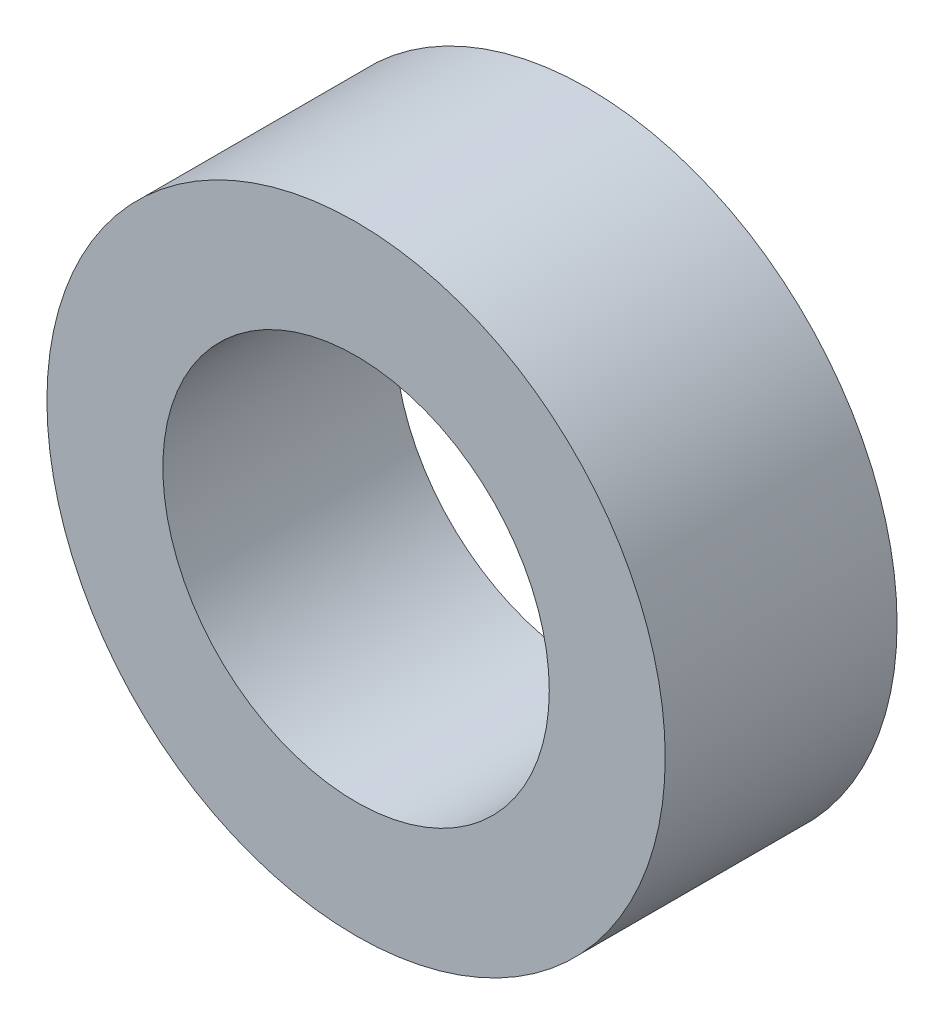
SolidWorks part; units mm, degrees
ref_plane "前视基准面" through (0, 0, 0) normal (0, 0, 1) x (1, 0, 0)
ref_plane "上视基准面" through (0, 0, 0) normal (0, 1, 0) x (1, 0, 0)
ref_plane "右视基准面" through (0, 0, 0) normal (1, 0, 0) x (0, 0, -1)
sketch "草图1" plane through (0, 0, 0) normal (0, 0, 1) x (1, 0, 0)
  circle A0 centre (0, 0) radius 8
  circle A1 centre (0, 0) radius 5
  dimension "D1" = 10
  dimension "D2" = 16
extrude "凸台-拉伸1" add sketch "草图1" along normal blind 6
